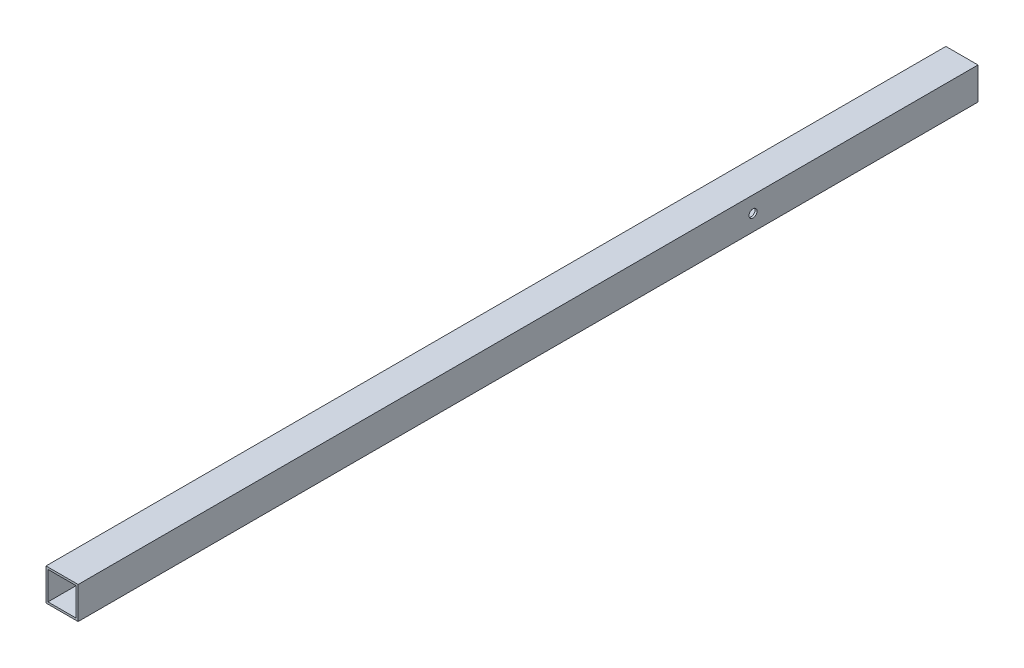
SolidWorks part; units mm, degrees
ref_plane "Front Plane" through (0, 0, 0) normal (0, 0, 1) x (1, 0, 0)
ref_plane "Top Plane" through (0, 0, 0) normal (0, 1, 0) x (1, 0, 0)
ref_plane "Right Plane" through (0, 0, 0) normal (1, 0, 0) x (0, 0, -1)
sketch "Sketch1" plane through (0, 0, 0) normal (0, 0, 1) x (1, 0, 0)
  line L0 (12.7, 0) -> (11.1125, 0) construction
  line L1 (-12.7, 0) -> (12.7, 0) construction
  line L2 (0, 12.7) -> (0, -12.7)
  point P7 (0, 0)
sketch "Sketch2" plane through (0, 0, 0) normal (1, 0, 0) x (0, 0, -1)
  line L0 (914.4, 0) -> (-914.4, 0)
  point P4 (0, 0)
  dimension "Length" = 1828.8
sketch "Sketch3" plane through (0, 0, 0) normal (0, 0, 1) x (1, 0, 0)
  line L5 (-12.7, -12.7) -> (12.7, -12.7)
  line L11 (-12.7, -12.7) -> (-12.7, 12.7)
  line L12 (-12.7, 12.7) -> (12.7, 12.7)
  line L13 (-11.1125, -11.1125) -> (11.1125, -11.1125)
  line L14 (12.7, -12.7) -> (12.7, 12.7)
  line L18 (-12.7, -12.7) -> (12.7, 12.7) construction
  line L19 (-12.7, 12.7) -> (12.7, -12.7) construction
  line L20 (-11.1125, -11.1125) -> (-11.1125, 11.1125)
  line L21 (-11.1125, 11.1125) -> (11.1125, 11.1125)
  line L22 (11.1125, -11.1125) -> (11.1125, 11.1125)
  line L23 (-11.1125, -11.1125) -> (11.1125, 11.1125) construction
  line L24 (-11.1125, 11.1125) -> (11.1125, -11.1125) construction
  point P0 (0, 0)
  point P1 (0, 0)
  point P10 (11.1125, -12.7)
  dimension "D2" = 1.5875
  dimension "D3" = 25.4
  dimension "D4" = 25.4
  dimension "D1" = 1.5875
extrude "Boss-Extrude1" add sketch "Sketch3" along normal up to vertex (914.4 mm away) and the other way up to vertex (914.4 mm away) up to point (0, 0, 914.4) other way up to point (0, 0, -914.4)
sketch "Sketch4" plane through (0, 0, 0) normal (1, 0, 0) x (0, 0, -1)
  line L0 (914.4, 0) -> (-914.4, 0) construction
  line L1 (-914.4, -12.7) -> (-914.4, 12.7) construction
  point P0 (-885.825, 0)
  point P6 (0, 0)
  point P8 (-876.3, 0)
  point P9 (876.3, 0)
  point P10 (885.825, 0)
  dimension "D1" = 28.575
  dimension "D2" = 38.1
  dimension "D3" = 28.575
  dimension "D4" = 38.1
sketch "Sketch5" plane through (0, 0, 914.4) normal (0, 0, 1) x (1, 0, 0)
  line L1 (15.2032, -13.6728) -> (-15.2032, -13.6728)
  line L2 (15.2032, -13.6728) -> (15.2032, 13.6728)
  line L3 (15.2032, 13.6728) -> (-15.2032, 13.6728)
  line L4 (-15.2032, -13.6728) -> (-15.2032, 13.6728)
  line L5 (15.2032, -13.6728) -> (-15.2032, 13.6728) construction
  line L6 (15.2032, 13.6728) -> (-15.2032, -13.6728) construction
  point P0 (0, 0)
extrude "Cut-Extrude1" cut sketch "Sketch5" against normal blind 1117.6
hole_wizard "1/4 (0.25) Diameter Hole1" positions "Sketch6" profile "Sketch7" hole size "1/4" standard "ANSI Inch" end condition through all
sketch "Sketch6" plane through (-12.7, 0, 0) normal (-1, 0, 0) x (0, 0, 1)
  line L0 (-914.4, 12.7) -> (-914.4, -12.7) construction
  point P0 (-736.6, 0)
  dimension "D1" = 177.8
sketch "Sketch7" plane through (-12.7, 0, -736.6) normal (0, 1, 0) x (0, 0, 1)
  line L0 (0, 0) -> (0, 25.4)
  line L1 (0, 25.4) -> (3.175, 25.4)
  line L2 (3.175, 25.4) -> (3.175, 0)
  line L5 (3.175, 0) -> (0, 0)
  line L11 (0, -6.35) -> (0, 107.95) construction
  dimension "Thru Hole Dia." = 6.35
  dimension "Thru Hole Depth" = 25.4
hole_wizard "3/16 (0.1875) Diameter Hole1" positions "Sketch8" profile "Sketch9" hole size "3/16" standard "ANSI Inch"
sketch "Sketch8" plane through (0, -12.7, 0) normal (0, -1, 0) x (-1, 0, 0)
  point P23 (0, 889)
  point P26 (0, 863.6)
  point P29 (0, 838.2)
  point P38 (0, 279.4)
  point P41 (0, 254)
  point P44 (0, 228.6)
sketch "Sketch9" plane through (0, -12.7, -889) normal (1, 0, 0) x (0, 0, -1)
  line L0 (0, 0) -> (0, 1.5875)
  line L1 (0, 1.5875) -> (2.3812, 1.5875)
  line L2 (2.3812, 1.5875) -> (2.3812, 0)
  line L5 (2.3812, 0) -> (0, 0)
  line L11 (0, -6.35) -> (0, 107.95) construction
  dimension "Thru Hole Dia." = 4.7625
  dimension "Thru Hole Depth" = 1.5875
hole_wizard "#10 Clearance Hole1" positions "Sketch10" profile "Sketch11" hole size "#10" standard "ANSI Inch"
sketch "Sketch10" plane through (0, -12.7, 0) normal (0, -1, 0) x (-1, 0, 0)
  point P13 (0, 635)
  point P16 (0, 584.2)
  point P19 (0, 533.4)
  point P22 (0, 482.6)
sketch "Sketch11" plane through (0, -12.7, -635) normal (1, 0, 0) x (0, 0, -1)
  line L0 (0, 0) -> (0, 1.5875)
  line L1 (0, 1.5875) -> (2.5527, 1.5875)
  line L2 (2.5527, 1.5875) -> (2.5527, 0)
  line L5 (2.5527, 0) -> (0, 0)
  line L11 (0, -6.35) -> (0, 107.95) construction
  dimension "Thru Hole Dia." = 5.1054
  dimension "Thru Hole Depth" = 1.5875
equation "\"D2@Sketch3\"=\"Wall Thickness@Sketch1\""
equation "\"D1@Sketch4\"=\"Width@Sketch1\"*1.125"
equation "\"D2@Sketch4\"=\"Width@Sketch1\"*1.5"
equation "\"D3@Sketch4\"=\"D1@Sketch4\""
equation "\"D4@Sketch4\"=\"D2@Sketch4\""
